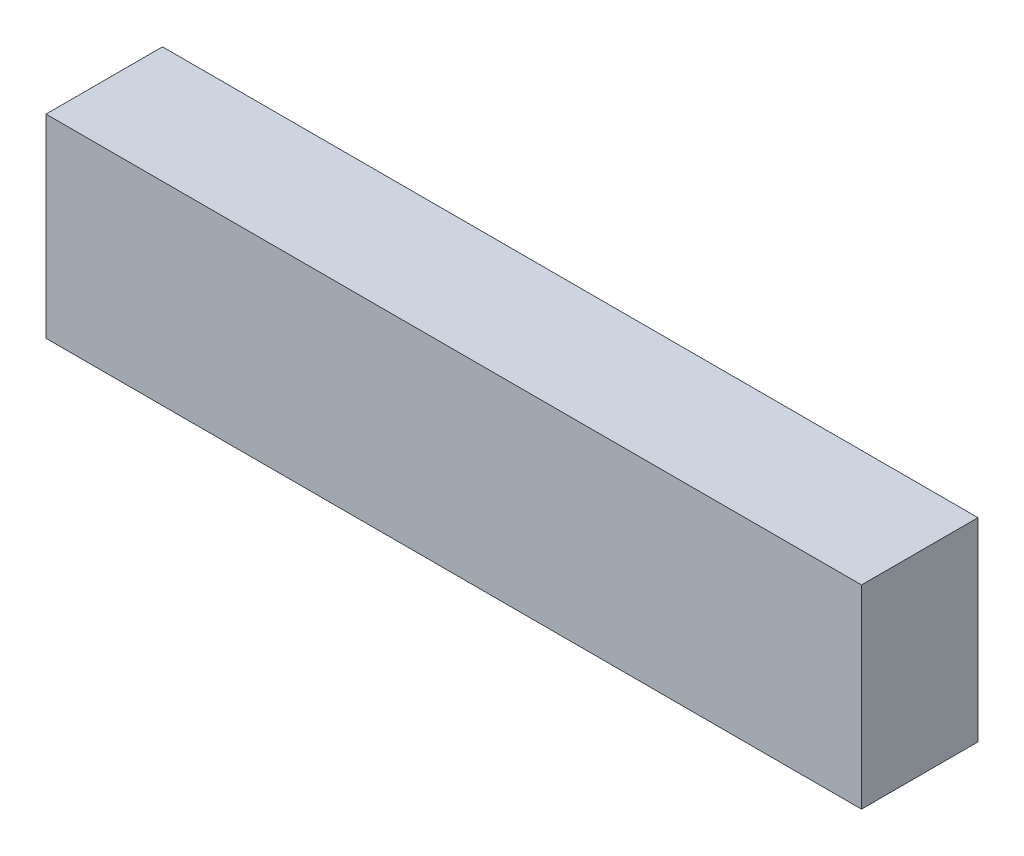
SolidWorks part; units mm, degrees
ref_plane "前视" through (0, 0, 0) normal (0, 0, 1) x (1, 0, 0)
ref_plane "上视" through (0, 0, 0) normal (0, 1, 0) x (1, 0, 0)
ref_plane "右视" through (0, 0, 0) normal (1, 0, 0) x (0, 0, -1)
sketch "草图1" plane through (0, 0, 0) normal (0, 0, 1) x (1, 0, 0)
  line L1 (0, 166.7) -> (700, 166.7)
  line L2 (0, 166.7) -> (0, 0)
  line L3 (0, 0) -> (700, 0)
  line L4 (700, 166.7) -> (700, 0)
  dimension "D1" = 700
  dimension "D2" = 166.7
extrude "基体-拉伸" add sketch "草图1" along normal blind 100
